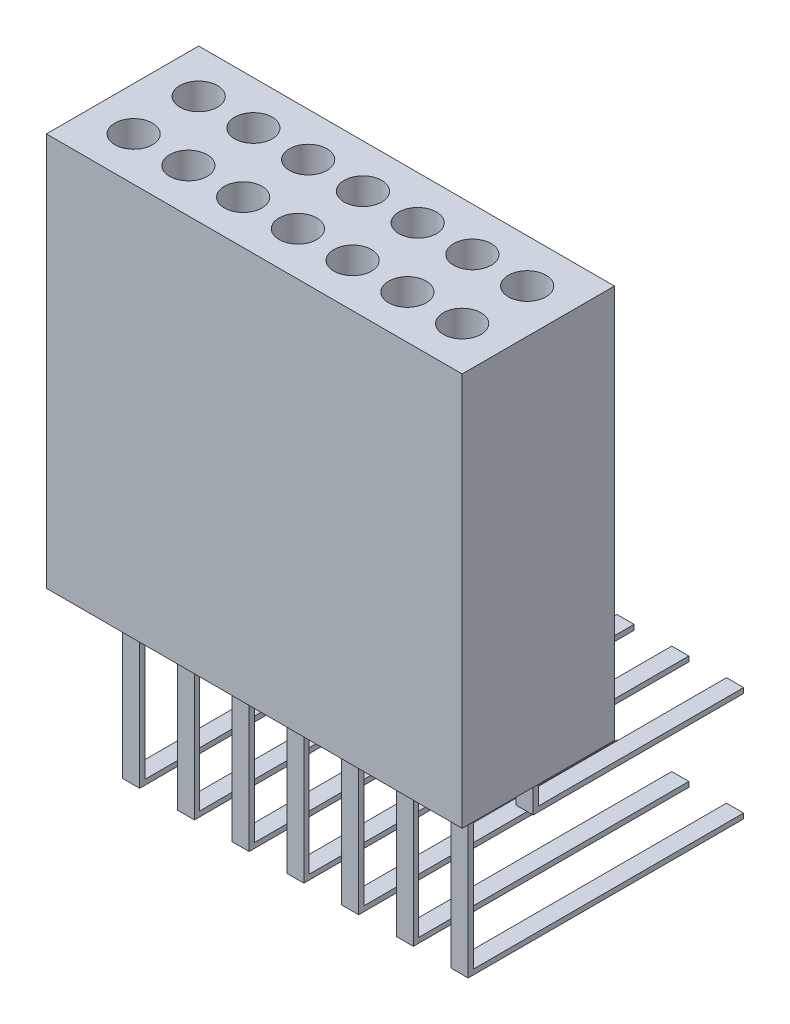
SolidWorks part; units mm, degrees
material "PEI"
ref_plane "Front Plane" through (0, 0, 0) normal (0, 0, 1) x (1, 0, 0)
ref_plane "Top Plane" through (0, 0, 0) normal (0, 1, 0) x (1, 0, 0)
ref_plane "Right Plane" through (0, 0, 0) normal (1, 0, 0) x (0, 0, -1)
sketch "Sketch2" plane through (0, 0, 0) normal (0, 1, 0) x (1, 0, 0)
  line L1 (0, 0) -> (4.86, 0)
  line L2 (0, 0) -> (0, 1.78)
  line L3 (0, 1.78) -> (4.86, 1.78)
  line L4 (4.86, 0) -> (4.86, 1.78)
  dimension "D1" = 4.86
  dimension "D2" = 1.78
extrude "Boss-Extrude1" add sketch "Sketch2" along normal blind 4.6
sketch "Sketch3" plane through (0, 4.6, 0) normal (0, 1, 0) x (1, 0, 0)
  line L0 (4.86, 1.78) -> (0, 1.78) construction
  line L1 (0, 1.78) -> (0, 0) construction
  circle A0 centre (0.51, 1.27) radius 0.22
  circle A1 centre (1.15, 1.27) radius 0.22
  circle A2 centre (1.79, 1.27) radius 0.22
  circle A3 centre (2.43, 1.27) radius 0.22
  circle A4 centre (3.07, 1.27) radius 0.22
  circle A5 centre (3.71, 1.27) radius 0.22
  circle A6 centre (4.35, 1.27) radius 0.22
  circle A7 centre (1.15, 0.51) radius 0.22
  circle A8 centre (1.79, 0.51) radius 0.22
  circle A9 centre (2.43, 0.51) radius 0.22
  circle A10 centre (3.07, 0.51) radius 0.22
  circle A11 centre (3.71, 0.51) radius 0.22
  circle A12 centre (4.35, 0.51) radius 0.22
  circle A13 centre (0.51, 0.51) radius 0.22
  dimension "D1" = 2
  dimension "D3" = 0.51
  dimension "D4" = 0.51
extrude "Cut-Extrude1" cut sketch "Sketch3" against normal blind 4.5
sketch "Sketch4" plane through (0, 0, 0) normal (0, -1, 0) x (1, 0, 0)
  line L0 (0, 0) -> (4.86, 0) construction
  line L1 (0.41, -0.48) -> (0.61, -0.48)
  line L2 (0.41, -0.48) -> (0.41, -0.54)
  line L3 (0.41, -0.54) -> (0.61, -0.54)
  line L4 (0.61, -0.48) -> (0.61, -0.54)
  line L5 (0.41, -0.48) -> (0.61, -0.54) construction
  line L6 (0.41, -0.54) -> (0.61, -0.48) construction
  line L7 (0, -1.78) -> (0, 0) construction
  line L8 (1.05, -0.48) -> (1.25, -0.48)
  line L9 (1.05, -0.48) -> (1.05, -0.54)
  line L10 (1.05, -0.54) -> (1.25, -0.54)
  line L11 (1.25, -0.48) -> (1.25, -0.54)
  line L12 (1.05, -0.48) -> (1.25, -0.54) construction
  line L13 (1.05, -0.54) -> (1.25, -0.48) construction
  line L14 (1.69, -0.48) -> (1.89, -0.48)
  line L15 (1.69, -0.48) -> (1.69, -0.54)
  line L16 (1.69, -0.54) -> (1.89, -0.54)
  line L17 (1.89, -0.48) -> (1.89, -0.54)
  line L18 (1.69, -0.48) -> (1.89, -0.54) construction
  line L19 (1.69, -0.54) -> (1.89, -0.48) construction
  line L20 (2.33, -0.48) -> (2.53, -0.48)
  line L21 (2.33, -0.48) -> (2.33, -0.54)
  line L22 (2.33, -0.54) -> (2.53, -0.54)
  line L23 (2.53, -0.48) -> (2.53, -0.54)
  line L24 (2.33, -0.48) -> (2.53, -0.54) construction
  line L25 (2.33, -0.54) -> (2.53, -0.48) construction
  line L26 (2.97, -0.48) -> (3.17, -0.48)
  line L27 (2.97, -0.48) -> (2.97, -0.54)
  line L28 (2.97, -0.54) -> (3.17, -0.54)
  line L29 (3.17, -0.48) -> (3.17, -0.54)
  line L30 (2.97, -0.48) -> (3.17, -0.54) construction
  line L31 (2.97, -0.54) -> (3.17, -0.48) construction
  line L32 (3.61, -0.48) -> (3.81, -0.48)
  line L33 (3.61, -0.48) -> (3.61, -0.54)
  line L34 (3.61, -0.54) -> (3.81, -0.54)
  line L35 (3.81, -0.48) -> (3.81, -0.54)
  line L36 (3.61, -0.48) -> (3.81, -0.54) construction
  line L37 (3.61, -0.54) -> (3.81, -0.48) construction
  line L38 (4.25, -0.48) -> (4.45, -0.48)
  line L39 (4.25, -0.48) -> (4.25, -0.54)
  line L40 (4.25, -0.54) -> (4.45, -0.54)
  line L41 (4.45, -0.48) -> (4.45, -0.54)
  line L42 (4.25, -0.48) -> (4.45, -0.54) construction
  line L43 (4.25, -0.54) -> (4.45, -0.48) construction
  point P0 (0.51, -0.51)
  point P11 (1.15, -0.51)
  point P16 (1.79, -0.51)
  point P21 (2.43, -0.51)
  point P26 (3.07, -0.51)
  point P31 (3.71, -0.51)
  point P36 (4.35, -0.51)
  point P41 (1.79, -0.51)
  dimension "D1" = 0.2
  dimension "D2" = 0.06
  dimension "D3" = 0.51
  dimension "D4" = 0.51
  dimension "D6" = 1.28
  dimension "D5" = 7
extrude "Boss-Extrude2" add sketch "Sketch4" along normal blind 1.96
sketch "Sketch6" plane through (0, 0, 0) normal (0, -1, 0) x (1, 0, 0)
  line L0 (0, -1.78) -> (0, 0) construction
  line L1 (0.41, -1.24) -> (0.61, -1.24)
  line L2 (0.41, -1.24) -> (0.41, -1.3)
  line L3 (0.41, -1.3) -> (0.61, -1.3)
  line L4 (0.61, -1.24) -> (0.61, -1.3)
  line L5 (0.41, -1.24) -> (0.61, -1.3) construction
  line L6 (0.41, -1.3) -> (0.61, -1.24) construction
  line L7 (4.86, -1.78) -> (0, -1.78) construction
  line L8 (1.05, -1.24) -> (1.25, -1.24)
  line L9 (1.05, -1.24) -> (1.05, -1.3)
  line L10 (1.05, -1.3) -> (1.25, -1.3)
  line L11 (1.25, -1.24) -> (1.25, -1.3)
  line L12 (1.05, -1.24) -> (1.25, -1.3) construction
  line L13 (1.05, -1.3) -> (1.25, -1.24) construction
  line L14 (1.69, -1.24) -> (1.89, -1.24)
  line L15 (1.69, -1.24) -> (1.69, -1.3)
  line L16 (1.69, -1.3) -> (1.89, -1.3)
  line L17 (1.89, -1.24) -> (1.89, -1.3)
  line L18 (1.69, -1.24) -> (1.89, -1.3) construction
  line L19 (1.69, -1.3) -> (1.89, -1.24) construction
  line L20 (2.33, -1.24) -> (2.53, -1.24)
  line L21 (2.33, -1.24) -> (2.33, -1.3)
  line L22 (2.33, -1.3) -> (2.53, -1.3)
  line L23 (2.53, -1.24) -> (2.53, -1.3)
  line L24 (2.33, -1.24) -> (2.53, -1.3) construction
  line L25 (2.33, -1.3) -> (2.53, -1.24) construction
  line L26 (2.97, -1.24) -> (3.17, -1.24)
  line L27 (2.97, -1.24) -> (2.97, -1.3)
  line L28 (2.97, -1.3) -> (3.17, -1.3)
  line L29 (3.17, -1.24) -> (3.17, -1.3)
  line L30 (2.97, -1.24) -> (3.17, -1.3) construction
  line L31 (2.97, -1.3) -> (3.17, -1.24) construction
  line L32 (3.61, -1.24) -> (3.81, -1.24)
  line L33 (3.61, -1.24) -> (3.61, -1.3)
  line L34 (3.61, -1.3) -> (3.81, -1.3)
  line L35 (3.81, -1.24) -> (3.81, -1.3)
  line L36 (3.61, -1.24) -> (3.81, -1.3) construction
  line L37 (3.61, -1.3) -> (3.81, -1.24) construction
  line L38 (4.25, -1.24) -> (4.45, -1.24)
  line L39 (4.25, -1.24) -> (4.25, -1.3)
  line L40 (4.25, -1.3) -> (4.45, -1.3)
  line L41 (4.45, -1.24) -> (4.45, -1.3)
  line L42 (4.25, -1.24) -> (4.45, -1.3) construction
  line L43 (4.25, -1.3) -> (4.45, -1.24) construction
  point P0 (0.51, -1.27)
  point P10 (1.15, -1.27)
  point P15 (1.79, -1.27)
  point P20 (2.43, -1.27)
  point P25 (3.07, -1.27)
  point P30 (3.71, -1.27)
  point P35 (4.35, -1.27)
  dimension "D1" = 0.2
  dimension "D2" = 0.06
  dimension "D3" = 0.51
  dimension "D4" = 0.51
  dimension "D6" = 0.64
  dimension "D5" = 7
extrude "Boss-Extrude3" add sketch "Sketch6" along normal blind 0.69
sketch "Sketch7" plane through (0, 0, -1.3) normal (0, 0, -1) x (-1, 0, 0)
  line L0 (-4.25, -0.69) -> (-4.25, 0) construction
  line L1 (-4.45, -0.69) -> (-4.25, -0.69)
  line L2 (-4.45, -0.69) -> (-4.45, -0.63)
  line L3 (-4.45, -0.63) -> (-4.25, -0.63)
  line L4 (-4.25, -0.69) -> (-4.25, -0.63)
  line L5 (-3.81, -0.69) -> (-3.61, -0.69)
  line L6 (-3.81, -0.69) -> (-3.81, -0.63)
  line L7 (-3.81, -0.63) -> (-3.61, -0.63)
  line L8 (-3.61, -0.69) -> (-3.61, -0.63)
  line L9 (-3.17, -0.69) -> (-2.97, -0.69)
  line L10 (-3.17, -0.69) -> (-3.17, -0.63)
  line L11 (-3.17, -0.63) -> (-2.97, -0.63)
  line L12 (-2.97, -0.69) -> (-2.97, -0.63)
  line L13 (-2.53, -0.69) -> (-2.33, -0.69)
  line L14 (-2.53, -0.69) -> (-2.53, -0.63)
  line L15 (-2.53, -0.63) -> (-2.33, -0.63)
  line L16 (-2.33, -0.69) -> (-2.33, -0.63)
  line L17 (-1.89, -0.69) -> (-1.69, -0.69)
  line L18 (-1.89, -0.69) -> (-1.89, -0.63)
  line L19 (-1.89, -0.63) -> (-1.69, -0.63)
  line L20 (-1.69, -0.69) -> (-1.69, -0.63)
  line L21 (-1.25, -0.69) -> (-1.05, -0.69)
  line L22 (-1.25, -0.69) -> (-1.25, -0.63)
  line L23 (-1.25, -0.63) -> (-1.05, -0.63)
  line L24 (-1.05, -0.69) -> (-1.05, -0.63)
  line L25 (-0.61, -0.69) -> (-0.41, -0.69)
  line L26 (-0.61, -0.69) -> (-0.61, -0.63)
  line L27 (-0.61, -0.63) -> (-0.41, -0.63)
  line L28 (-0.41, -0.69) -> (-0.41, -0.63)
  dimension "D1" = 0.06
extrude "Boss-Extrude4" add sketch "Sketch7" along normal blind 2.4
sketch "Sketch8" plane through (0, 0, -0.54) normal (0, 0, -1) x (-1, 0, 0)
  line L0 (-4.25, -1.96) -> (-4.45, -1.96) construction
  line L1 (-4.45, -1.96) -> (-4.25, -1.96)
  line L2 (-4.45, -1.96) -> (-4.45, -1.9)
  line L3 (-4.45, -1.9) -> (-4.25, -1.9)
  line L4 (-4.25, -1.96) -> (-4.25, -1.9)
  line L5 (-4.45, -1.96) -> (-4.45, 0) construction
  line L6 (-4.25, -1.96) -> (-4.25, 0) construction
  line L7 (-3.81, -1.96) -> (-3.61, -1.96)
  line L8 (-3.81, -1.96) -> (-3.81, -1.9)
  line L9 (-3.81, -1.9) -> (-3.61, -1.9)
  line L10 (-3.61, -1.96) -> (-3.61, -1.9)
  line L11 (-3.17, -1.96) -> (-2.97, -1.96)
  line L12 (-3.17, -1.96) -> (-3.17, -1.9)
  line L13 (-3.17, -1.9) -> (-2.97, -1.9)
  line L14 (-2.97, -1.96) -> (-2.97, -1.9)
  line L15 (-2.53, -1.96) -> (-2.33, -1.96)
  line L16 (-2.53, -1.96) -> (-2.53, -1.9)
  line L17 (-2.53, -1.9) -> (-2.33, -1.9)
  line L18 (-2.33, -1.96) -> (-2.33, -1.9)
  line L19 (-1.89, -1.96) -> (-1.69, -1.96)
  line L20 (-1.89, -1.96) -> (-1.89, -1.9)
  line L21 (-1.89, -1.9) -> (-1.69, -1.9)
  line L22 (-1.69, -1.96) -> (-1.69, -1.9)
  line L23 (-1.25, -1.96) -> (-1.05, -1.96)
  line L24 (-1.25, -1.96) -> (-1.25, -1.9)
  line L25 (-1.25, -1.9) -> (-1.05, -1.9)
  line L26 (-1.05, -1.96) -> (-1.05, -1.9)
  line L27 (-0.61, -1.96) -> (-0.41, -1.96)
  line L28 (-0.61, -1.96) -> (-0.61, -1.9)
  line L29 (-0.61, -1.9) -> (-0.41, -1.9)
  line L30 (-0.41, -1.96) -> (-0.41, -1.9)
  dimension "D1" = 0.06
extrude "Boss-Extrude5" add sketch "Sketch8" along normal blind 3.16
